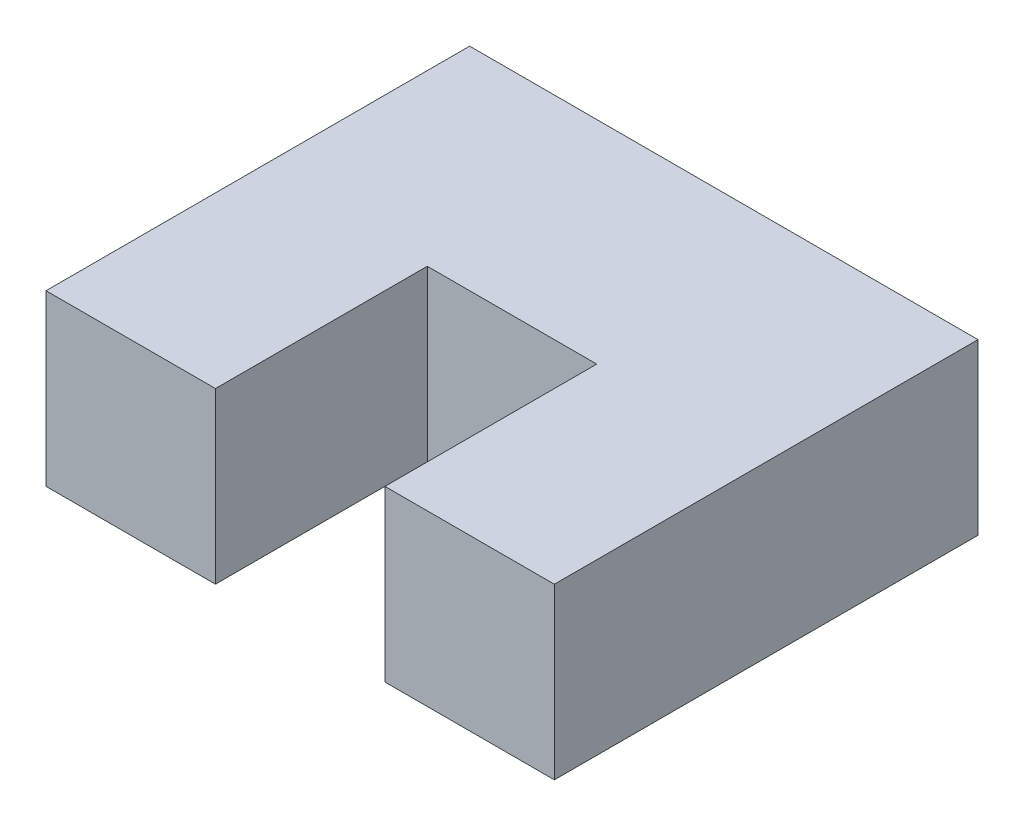
SolidWorks part; units mm, degrees
ref_plane "Alzado" through (0, 0, 0) normal (0, 0, 1) x (1, 0, 0)
ref_plane "Planta" through (0, 0, 0) normal (0, 1, 0) x (1, 0, 0)
ref_plane "Vista lateral" through (0, 0, 0) normal (1, 0, 0) x (0, 0, -1)
sketch "Croquis1" plane through (0, 0, 0) normal (0, 0, 1) x (1, 0, 0)
  line L1 (-30, -10) -> (30, -10)
  line L2 (-30, -10) -> (-30, 10)
  line L3 (-30, 10) -> (30, 10)
  line L4 (30, -10) -> (30, 10)
  line L5 (-30, -10) -> (30, 10) construction
  line L6 (-30, 10) -> (30, -10) construction
  point P0 (0, 0)
  dimension "D1" = 60
  dimension "D2" = 20
extrude "Saliente-Extruir1" add sketch "Croquis1" along normal blind 30
sketch "Croquis2" plane through (0, 0, 30) normal (0, 0, 1) x (1, 0, 0)
  line L0 (30, 10) -> (-30, 10) construction
  line L1 (-10, -10) -> (10, -10)
  line L2 (-10, -10) -> (-10, 10)
  line L3 (-10, 10) -> (10, 10)
  line L4 (10, -10) -> (10, 10)
  line L5 (-10, -10) -> (10, 10) construction
  line L6 (-10, 10) -> (10, -10) construction
  point P0 (0, 0)
  dimension "D1" = 20
  dimension "D2" = 20
extrude "Cortar-Extruir1" cut sketch "Croquis2" against normal blind 5
sketch "Croquis4" plane through (0, 0, 30) normal (0, 0, 1) x (1, 0, 0)
  line L0 (-30, -10) -> (-10, -10) construction
  line L1 (-30, -10) -> (-10, -10)
  line L2 (-30, -10) -> (-30, 10)
  line L3 (-30, 10) -> (-10, 10)
  line L4 (-10, -10) -> (-10, 10)
  line L5 (-10, 10) -> (-30, 10) construction
  line L6 (-10, 10) -> (-10, -10) construction
  line L7 (10, -10) -> (10, 10) construction
  line L8 (10, 10) -> (30, 10)
  line L9 (10, 10) -> (10, -10)
  line L10 (10, -10) -> (30, -10)
  line L11 (30, 10) -> (30, -10)
extrude "Saliente-Extruir2" add sketch "Croquis4" along normal blind 20
